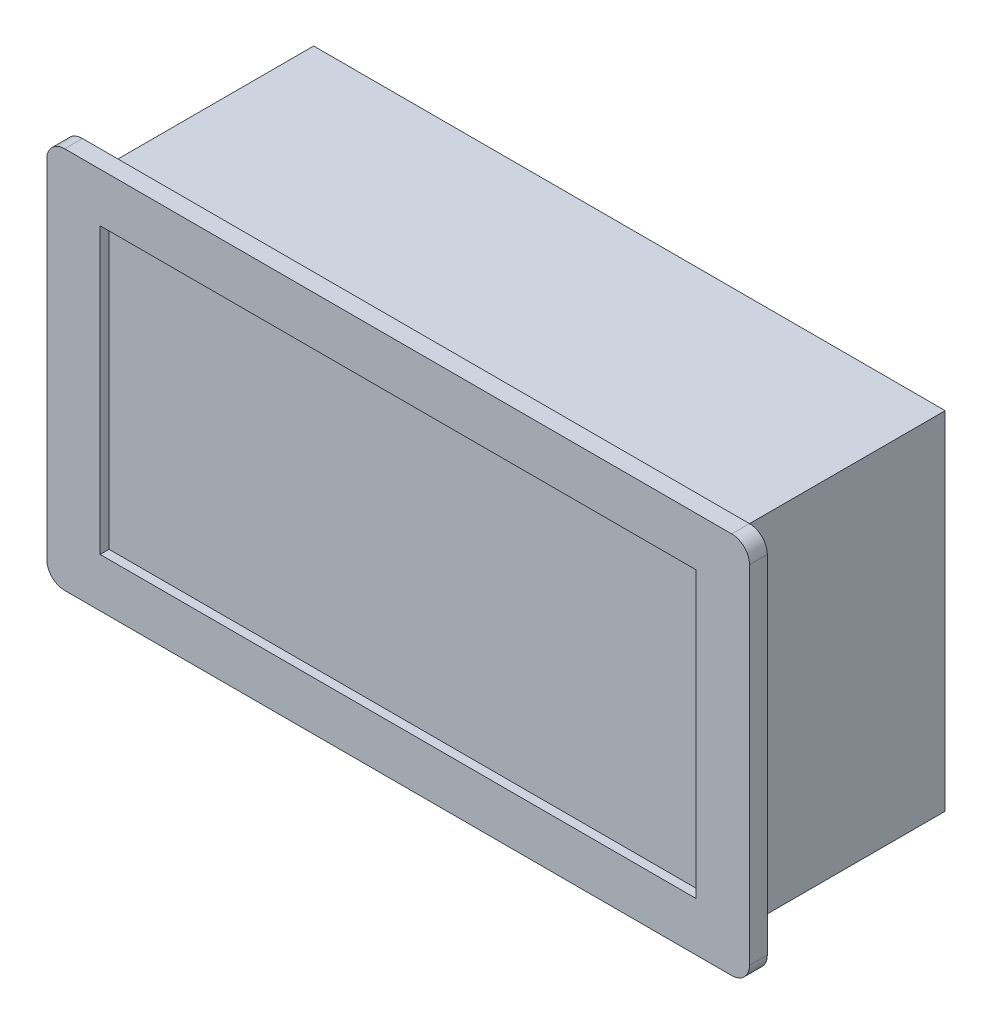
SolidWorks part; units mm, degrees
ref_plane "前视基准面" through (0, 0, 0) normal (0, 0, 1) x (1, 0, 0)
ref_plane "上视基准面" through (0, 0, 0) normal (0, 1, 0) x (1, 0, 0)
ref_plane "右视基准面" through (0, 0, 0) normal (1, 0, 0) x (0, 0, -1)
sketch "草图1" plane through (0, 0, 0) normal (0, 0, 1) x (1, 0, 0)
  line L1 (35.5, -19.5) -> (-35.5, -19.5)
  line L2 (35.5, -19.5) -> (35.5, 19.5)
  line L3 (35.5, 19.5) -> (-35.5, 19.5)
  line L4 (-35.5, -19.5) -> (-35.5, 19.5)
  line L5 (35.5, -19.5) -> (-35.5, 19.5) construction
  line L6 (35.5, 19.5) -> (-35.5, -19.5) construction
  point P0 (0, 0)
  dimension "D1" = 71
  dimension "D2" = 39
extrude "凸台-拉伸1" add sketch "草图1" along normal blind 24
sketch "草图2" plane through (0, 0, 24) normal (0, 0, 1) x (1, 0, 0)
  line L1 (-37.5, -21.5) -> (37.5, -21.5)
  line L2 (-39.5, -19.5) -> (-39.5, 19.5)
  line L3 (-37.5, 21.5) -> (37.5, 21.5)
  line L4 (39.5, -19.5) -> (39.5, 19.5)
  line L5 (-39.5, -21.5) -> (39.5, 21.5) construction
  line L6 (-39.5, 21.5) -> (39.5, -21.5) construction
  arc A0 (-37.5, -21.5) -> (-39.5, -19.5) centre (-37.5, -19.5) cw
  arc A1 (37.5, -21.5) -> (39.5, -19.5) centre (37.5, -19.5) ccw
  arc A2 (37.5, 21.5) -> (39.5, 19.5) centre (37.5, 19.5) cw
  arc A3 (-39.5, 19.5) -> (-37.5, 21.5) centre (-37.5, 19.5) cw
  point P0 (0, 0)
  dimension "D3" = 2
  dimension "D1" = 79
  dimension "D2" = 43
extrude "凸台-拉伸2" add sketch "草图2" along normal blind 2
sketch "草图3" plane through (0, 0, 26) normal (0, 0, 1) x (1, 0, 0)
  line L1 (-33.5, -16) -> (33.5, -16)
  line L2 (-33.5, -16) -> (-33.5, 16)
  line L3 (-33.5, 16) -> (33.5, 16)
  line L4 (33.5, -16) -> (33.5, 16)
  line L5 (-33.5, -16) -> (33.5, 16) construction
  line L6 (-33.5, 16) -> (33.5, -16) construction
  point P0 (0, 0)
  dimension "D1" = 67
  dimension "D2" = 32
extrude "切除-拉伸1" cut sketch "草图3" against normal blind 1
